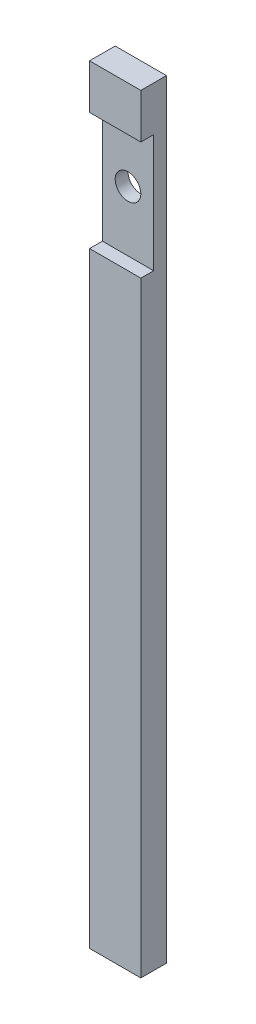
SolidWorks part; units mm, degrees
ref_plane "Front Plane" through (0, 0, 0) normal (0, 0, 1) x (1, 0, 0)
ref_plane "Top Plane" through (0, 0, 0) normal (0, 1, 0) x (1, 0, 0)
ref_plane "Right Plane" through (0, 0, 0) normal (1, 0, 0) x (0, 0, -1)
sketch "Sketch1" plane through (0, 0, 0) normal (0, 1, 0) x (1, 0, 0)
  line L1 (0, 0) -> (25.4, 0)
  line L2 (0, 0) -> (0, 12.7)
  line L3 (0, 12.7) -> (25.4, 12.7)
  line L4 (25.4, 0) -> (25.4, 12.7)
  dimension "D1" = 25.4
  dimension "D2" = 12.7
extrude "Boss-Extrude1" add sketch "Sketch1" along normal blind 381
sketch "Sketch2" plane through (0, 0, 0) normal (0, 0, 1) x (1, 0, 0)
  line L0 (0, 381) -> (25.4, 381) construction
  circle A0 centre (12.7, 330.2) radius 6.35
  point P5 (12.7, 381)
  dimension "D1" = 12.7
  dimension "D2" = 50.8
extrude "Cut-Extrude1" cut sketch "Sketch2" against normal through all from surface at 0 starting at face at (12.7, 190.5, 0)
sketch "Sketch3" plane through (0, 0, 0) normal (0, 0, 1) x (1, 0, 0)
  line L0 (0, 381) -> (0, 0) construction
  line L1 (0, 358.827) -> (25.4, 358.827)
  line L2 (0, 358.827) -> (0, 300.4125)
  line L3 (0, 300.4125) -> (25.4, 300.4125)
  line L4 (25.4, 358.827) -> (25.4, 300.4125)
  line L5 (25.4, 381) -> (25.4, 0) construction
extrude "Cut-Extrude2" cut sketch "Sketch3" against normal blind 6.35
